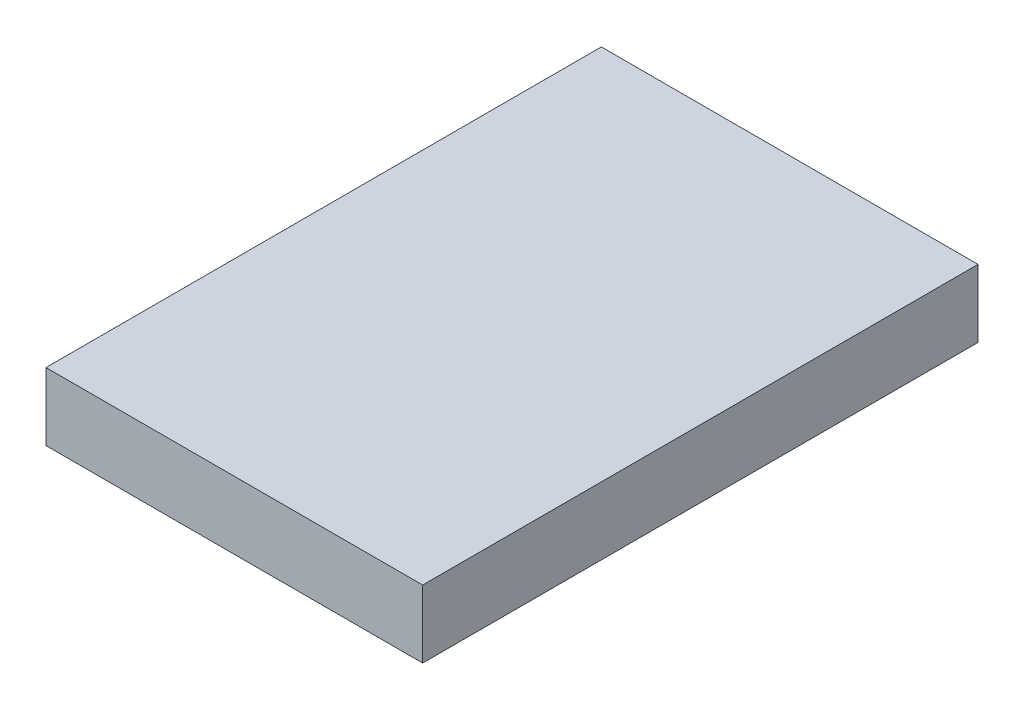
SolidWorks part; units mm, degrees
ref_plane "Front Plane" through (0, 0, 0) normal (0, 0, 1) x (1, 0, 0)
ref_plane "Top Plane" through (0, 0, 0) normal (0, 1, 0) x (1, 0, 0)
ref_plane "Right Plane" through (0, 0, 0) normal (1, 0, 0) x (0, 0, -1)
sketch "Sketch1" plane through (0, 0, 0) normal (0, 1, 0) x (1, 0, 0)
  line L1 (-39, -57.5) -> (39, -57.5)
  line L2 (-39, -57.5) -> (-39, 57.5)
  line L3 (-39, 57.5) -> (39, 57.5)
  line L4 (39, -57.5) -> (39, 57.5)
  line L5 (-39, -57.5) -> (39, 57.5) construction
  line L6 (-39, 57.5) -> (39, -57.5) construction
  point P0 (0, 0)
  dimension "D1" = 115
  dimension "D2" = 78
extrude "Boss-Extrude1" add sketch "Sketch1" along normal mid plane 14
